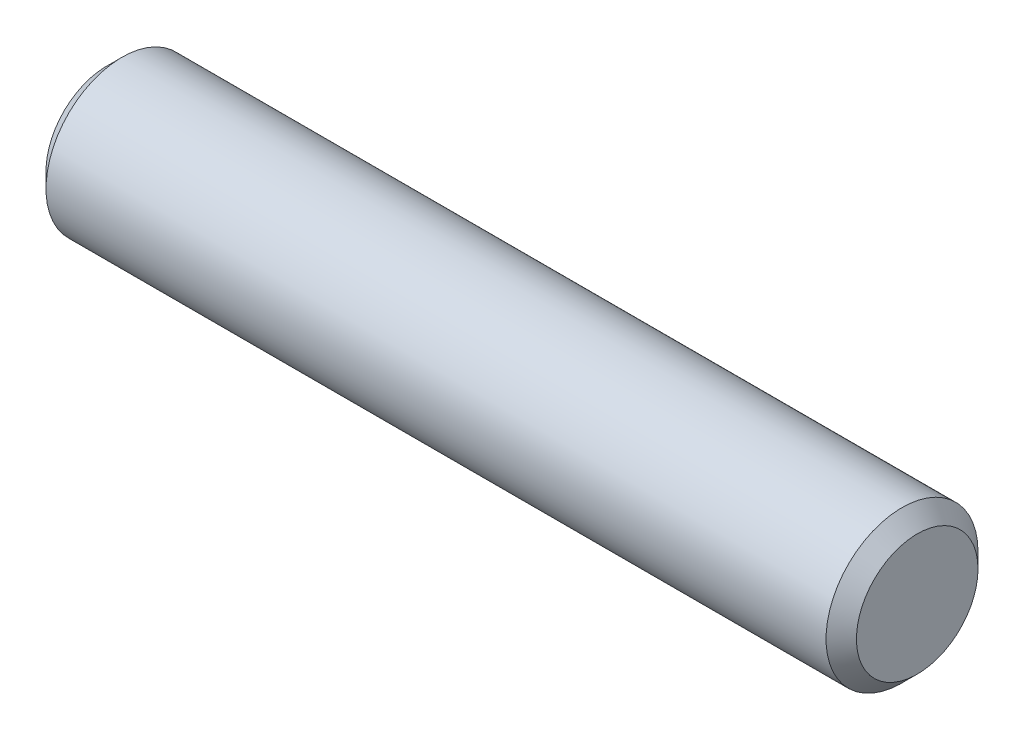
SolidWorks part; units mm, degrees
ref_plane "Front" through (0, 0, 0) normal (0, 0, 1) x (1, 0, 0)
ref_plane "Top" through (0, 0, 0) normal (0, 1, 0) x (1, 0, 0)
ref_plane "Right" through (0, 0, 0) normal (1, 0, 0) x (0, 0, -1)
sketch "Sketch1" plane through (0, 0, 0) normal (0, 0, 1) x (1, 0, 0)
  line L0 (-25.4, 0) -> (25.4, 0) construction
  line L1 (25.4, 4.7625) -> (25.4, -4.7625) construction
  line L2 (-25.4, 4.7625) -> (-25.4, -4.7625) construction
  dimension "Length" = 50.8
  dimension "Diameter" = 9.525
sketch "Sketch2" plane through (0, 0, 0) normal (1, 0, 0) x (0, 0, -1)
  circle A0 centre (0, 0) radius 4.7625
extrude "Extrude1" add sketch "Sketch2" against normal up to vertex (25.4 mm away) and the other way up to vertex (25.4 mm away) up to point (-25.4, 4.7625, 0) other way up to point (25.4, 4.7625, 0)
chamfer "Chamfer1" distance 0.9525 angle 45 2 edges at (25.4, 0, -4.7625) (-25.4, 0, -4.7625)
equation "\"D1@Chamfer1\" = \"Diameter@Sketch1\"*.1"
